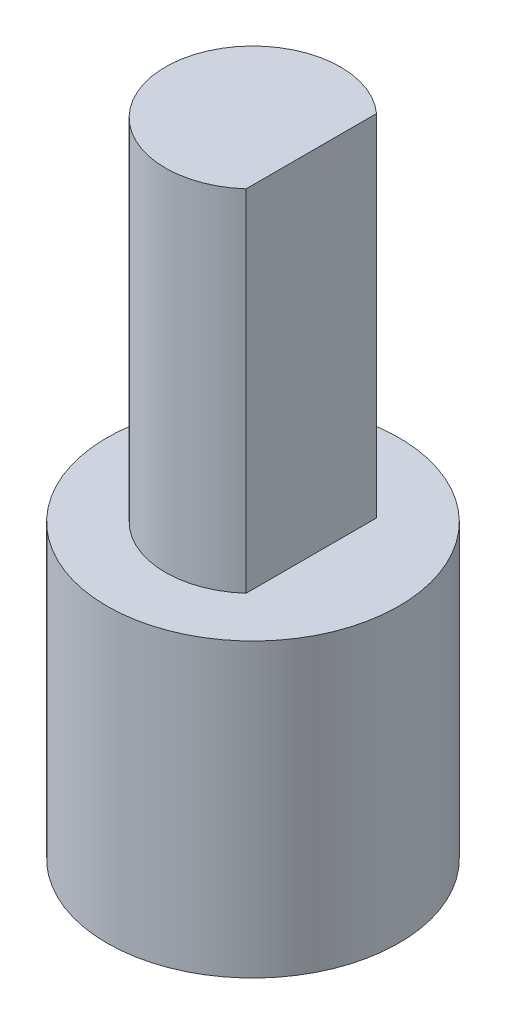
SolidWorks part; units mm, degrees
ref_plane "前视基准面" through (0, 0, 0) normal (0, 0, 1) x (1, 0, 0)
ref_plane "上视基准面" through (0, 0, 0) normal (0, 1, 0) x (1, 0, 0)
ref_plane "右视基准面" through (0, 0, 0) normal (1, 0, 0) x (0, 0, -1)
sketch "草图1" plane through (0, 0, 0) normal (0, 1, 0) x (1, 0, 0)
  circle A0 centre (0, 0) radius 2.5
extrude "凸台-拉伸1" add sketch "草图1" along normal blind 5
sketch "草图2" plane through (0, 5, 0) normal (0, 1, 0) x (1, 0, 0)
  line L1 (1, 1.118) -> (1, -1.118)
  arc A1 (1, -1.118) -> (1, 1.118) centre (0, 0) cw
extrude "凸台-拉伸2" add sketch "草图2" along normal blind 6
